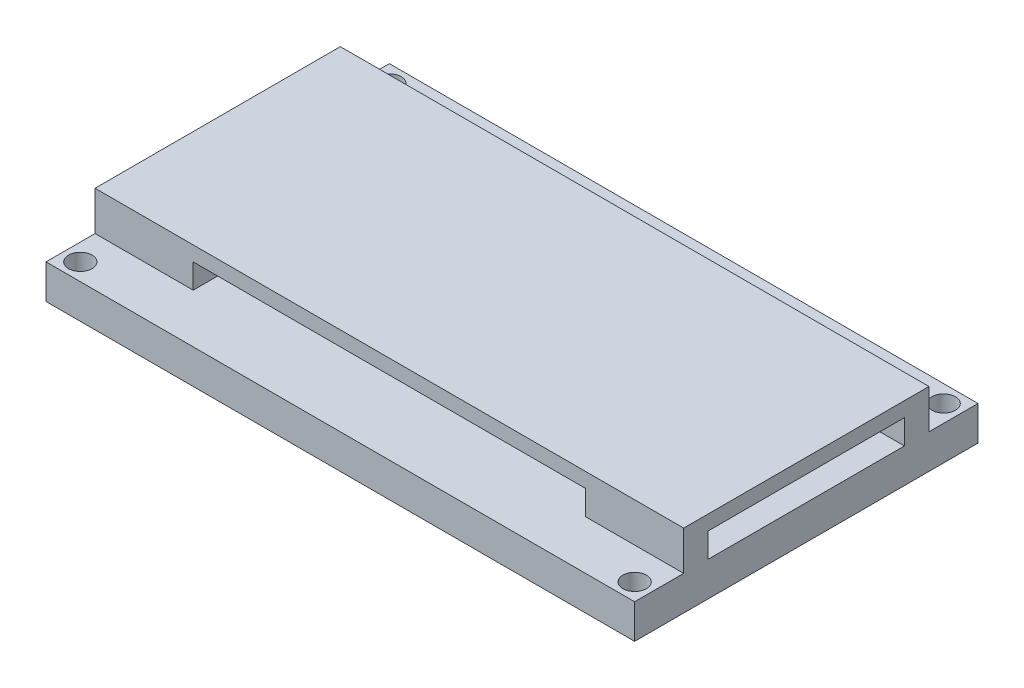
SolidWorks part; units mm, degrees
ref_plane "Alzado" through (0, 0, 0) normal (0, 0, 1) x (1, 0, 0)
ref_plane "Planta" through (0, 0, 0) normal (0, 1, 0) x (1, 0, 0)
ref_plane "Vista lateral" through (0, 0, 0) normal (1, 0, 0) x (0, 0, -1)
sketch "Croquis1" plane through (0, 0, 0) normal (0, 1, 0) x (1, 0, 0)
  line L1 (-60, 35) -> (60, 35)
  line L2 (-60, 35) -> (-60, -35)
  line L3 (-60, -35) -> (60, -35)
  line L4 (60, 35) -> (60, -35)
  line L5 (-60, 35) -> (60, -35) construction
  line L6 (-60, -35) -> (60, 35) construction
  point P0 (0, 0)
  dimension "D1" = 120
  dimension "D2" = 70
extrude "Saliente-Extruir1" add sketch "Croquis1" along normal blind 7
sketch "Croquis3" plane through (0, 7, 0) normal (0, 1, 0) x (1, 0, 0)
  line L0 (0, 0) -> (0, 42.0069) construction
  line L1 (0, 0) -> (79.2131, 0) construction
  line L2 (60, 31.5) -> (56.5, 31.5) construction
  line L3 (60, -35) -> (60, 35) construction
  line L4 (56.5, 35) -> (56.5, 31.5) construction
  line L5 (60, 35) -> (-60, 35) construction
  point P9 (-56.5, 31.5)
  point P12 (0, 0)
  point P13 (56.5, -31.5)
  point P14 (-56.5, -31.5)
  dimension "D1" = 3.5
  dimension "D2" = 3.5
hole_wizard "Taladro de margen para M41" positions "Croquis6" profile "Croquis7" hole size "M4" standard "DIN" end condition through all
sketch "Croquis6" plane through (0, 7, 0) normal (0, 1, 0) x (1, 0, 0)
  point P0 (56.5, 31.5)
  point P3 (56.5, -31.5)
  point P6 (-56.5, -31.5)
  point P9 (-56.5, 31.5)
sketch "Croquis7" plane through (56.5, 7, -31.5) normal (1, 0, 0) x (0, 0, 1)
  line L0 (0, 0) -> (0, 7)
  line L1 (0, 7) -> (2.4, 7)
  line L2 (2.4, 7) -> (2.4, 0)
  line L5 (2.4, 0) -> (0, 0)
  line L11 (0, -6.35) -> (0, 107.95) construction
  dimension "Diámetro de taladro hasta el siguiente" = 4.8
  dimension "Profundidad de taladro hasta el siguiente" = 7
sketch "Croquis8" plane through (0, 7, 0) normal (0, 1, 0) x (1, 0, 0)
  line L0 (-60, 25) -> (60, 25)
  line L1 (-60, 35) -> (-60, -35) construction
  line L2 (60, -35) -> (60, 35) construction
  line L3 (60, 25) -> (60, 20)
  line L4 (60, 20) -> (-60, 20)
  line L5 (-60, 20) -> (-60, 25)
  line L6 (-63.529, 0) -> (71.4567, 0) construction
  line L7 (0, 0) -> (79.2131, 0) construction
  line L8 (60, -20) -> (-60, -20)
  line L9 (60, -25) -> (60, -20)
  line L10 (-60, -25) -> (60, -25)
  line L11 (-60, -20) -> (-60, -25)
  dimension "D1" = 5
  dimension "D2" = 20
extrude "Saliente-Extruir2" add sketch "Croquis8" along normal blind 5
sketch "Croquis9" plane through (0, 12, 0) normal (0, 1, 0) x (1, 0, 0)
  line L1 (-60, 25) -> (60, 25)
  line L2 (-60, 25) -> (-60, -25)
  line L3 (-60, -25) -> (60, -25)
  line L4 (60, 25) -> (60, -25)
extrude "Saliente-Extruir3" add sketch "Croquis9" along normal blind 3
sketch "Croquis10" plane through (0, 0, 25) normal (0, 0, 1) x (1, 0, 0)
  line L0 (-60, 7) -> (60, 7) construction
  line L1 (-40, 7) -> (40, 7)
  line L2 (-40, 7) -> (-40, 12)
  line L3 (-40, 12) -> (40, 12)
  line L4 (40, 7) -> (40, 12)
  dimension "D1" = 80
  dimension "D2" = 5
  dimension "D3" = 40
extrude "Cortar-Extruir1" cut sketch "Croquis10" against normal through all
